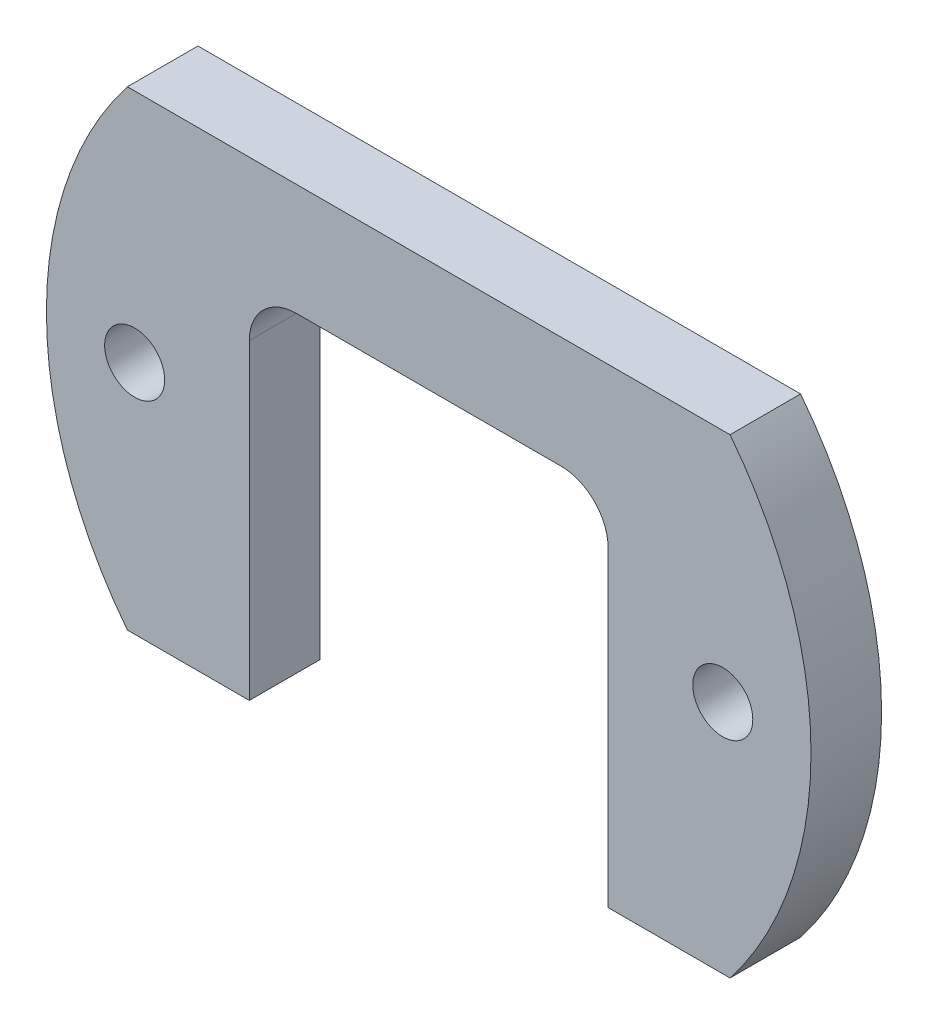
SolidWorks part; units mm, degrees
material "Q355"
ref_plane "前视基准面" through (0, 0, 0) normal (0, 0, 1) x (1, 0, 0)
ref_plane "上视基准面" through (0, 0, 0) normal (0, 1, 0) x (1, 0, 0)
ref_plane "右视基准面" through (0, 0, 0) normal (1, 0, 0) x (0, 0, -1)
sketch "草图1" plane through (0, 0, 0) normal (0, 0, 1) x (1, 0, 0)
  line L0 (0, 0) -> (0, 80) construction
  line L1 (-30.5, 61) -> (30.5, 61)
  line L2 (30.5, 61) -> (30.5, 0)
  line L3 (30.5, 0) -> (51.2348, 0)
  line L7 (0, 80) -> (51.2348, 80)
  line L16 (0, 80) -> (-51.2348, 80)
  line L19 (-30.5, 0) -> (-51.2348, 0)
  line L20 (-30.5, 61) -> (-30.5, 0)
  arc A0 (-51.2348, 80) -> (-51.2348, 0) centre (0, 40) ccw
  arc A1 (51.2348, 0) -> (51.2348, 80) centre (0, 40) ccw
  point P28 (0, 61)
  dimension "D7" = 130
  dimension "D1" = 61
  dimension "D2" = 61
  dimension "D10" = 80
extrude "凸台-拉伸1" add sketch "草图1" along normal blind 12
hole_wizard "M12 螺纹孔2" positions "草图6" profile "草图7" tap size "M12" standard "GB"
sketch "草图6" plane through (0, 0, 12) normal (0, 0, 1) x (1, 0, 0)
  line L0 (0, 80) -> (0, 0) construction
  line L1 (51.2348, 80) -> (-51.2348, 80) construction
  line L3 (-51.2348, 0) -> (-30.5, 0) construction
  point P0 (-50, 40)
  point P2 (50, 40)
  dimension "D1" = 100
  dimension "D2" = 40
sketch "草图7" plane through (-50, 40, 12) normal (1, 0, 0) x (0, -1, 0)
  line L0 (0, 0) -> (0, 35.8144)
  line L1 (0, 35.8144) -> (5.1, 32.75)
  line L2 (5.1, 32.75) -> (5.1, 0)
  line L5 (5.1, 0) -> (0, 0)
  line L10 (0, 35.8144) -> (-5.1, 32.75) construction
  line L11 (0, -6.35) -> (0, 107.95) construction
  dimension "螺纹孔钻头直径" = 10.2
  dimension "螺纹孔钻头深度" = 32.75
  dimension "导头角度" = 118
cosmetic thread "孔螺蚊线3" parameters "D1"=16, "D2"=12
cosmetic thread "孔螺蚊线4" parameters "D1"=16, "D2"=12
fillet "圆角2" radius 8 2 edges at (30.5, 61, 6) (-30.5, 61, 6)
